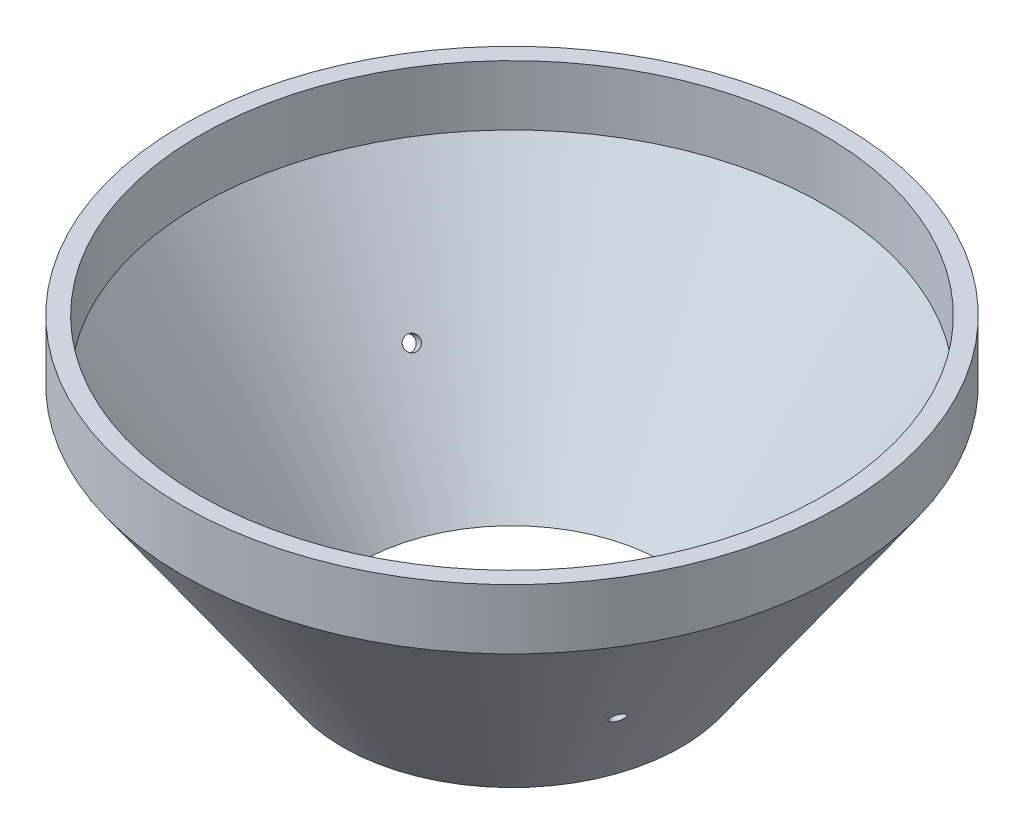
SolidWorks part; units mm, degrees
ref_plane "Front Plane" through (0, 0, 0) normal (0, 0, 1) x (1, 0, 0)
ref_plane "Top Plane" through (0, 0, 0) normal (0, 1, 0) x (1, 0, 0)
ref_plane "Right Plane" through (0, 0, 0) normal (1, 0, 0) x (0, 0, -1)
sketch3d "3DSketch4"
  line L0 (0, 30, 0) -> (-4.8009, 30, -2.4462) construction
  line L1 (0, 0, 0) -> (0, 30, 0) construction
  line L8 (16.2383, 26, 8.2738) -> (42.8895, 26, 21.8533) construction
sketch "Sketch23" plane through (0, 0, 0) normal (0, 0, -1) x (-1, 0, 0)
  line L0 (0, 0) -> (0, 30) construction
  line L1 (0, 24.8957) -> (-27.4634, 24.8957)
  line L3 (-14.092, 5.7993) -> (-27.4634, 24.8957)
  line L4 (0, 0.1163) -> (0, 14.6295) construction
  line L5 (0, 24.8957) -> (0, 5.7993)
  line L7 (0, 5.7993) -> (-14.092, 5.7993)
sketch "Sketch25" plane through (0, 0, 0) normal (0, 0, -1) x (-1, 0, 0)
  line L1 (0, 30) -> (-29.6127, 30.0574)
  line L3 (-10.4486, 2.6881) -> (-29.6127, 30.0574)
  line L4 (0, 0) -> (0, 30) construction
  line L5 (0, 30) -> (0, 2.6669)
  line L7 (-10.4486, 2.6881) -> (0, 2.6669)
revolve "Revolve3" add sketch "Sketch23" angle 360 about L1
revolve "Cut-Revolve3" cut sketch "Sketch25" angle 360 about L1
sketch "Sketch26" plane through (0, 24.8957, 0) normal (0, 1, 0) x (1, 0, 0)
  circle A0 centre (0, 0) radius 27.4634
extrude "Boss-Extrude1" add sketch "Sketch26" along normal blind 5
sketch "Sketch27" plane through (0, 29.8957, 0) normal (0, 1, 0) x (1, 0, 0)
  circle A0 centre (0, 0) radius 25.9985
extrude "Cut-Extrude1" cut sketch "Sketch27" against normal blind 5
hole_wizard "Ø0.55 (0.55) Diameter Hole2" positions "3DSketch8" profile "Sketch31" hole size "Ø0.55" standard "ANSI Metric"
sketch3d "3DSketch8"
  point P0 (17.9026, 14.3691, 9.1219)
sketch "Sketch31" plane through (17.9026, 14.3691, 9.1219) normal (0.1918, 0.694, 0.694) x (0.6561, 0.4352, -0.6165)
  line L0 (0, 0) -> (0, 2.3515)
  line L1 (0, 2.3515) -> (0.585, 2)
  line L2 (0.585, 2) -> (0.585, 0)
  line L5 (0.585, 0) -> (0, 0)
  line L10 (0, 2.3515) -> (-0.585, 2) construction
  line L11 (0, -6.35) -> (0, 107.95) construction
  dimension "Hole Dia." = 1.17
  dimension "Hole Depth" = 2
  dimension "Drill Angle" = 118
hole_wizard "Ø0.55 (0.55) Diameter Hole4" positions "3DSketch9" profile "Sketch32" hole size "Ø0.55" standard "ANSI Metric"
sketch3d "3DSketch9"
  point P1 (-17.9026, 14.3691, -9.1219)
sketch "Sketch32" plane through (-17.9026, 14.3691, -9.1219) normal (-0.6754, 0.5214, 0.5214) x (0.1052, -0.6318, 0.768)
  line L0 (0, 0) -> (0, 2.3515)
  line L1 (0, 2.3515) -> (0.585, 2)
  line L2 (0.585, 2) -> (0.585, 0)
  line L5 (0.585, 0) -> (0, 0)
  line L10 (0, 2.3515) -> (-0.585, 2) construction
  line L11 (0, -6.35) -> (0, 107.95) construction
  dimension "Hole Dia." = 1.17
  dimension "Hole Depth" = 2
  dimension "Drill Angle" = 118
